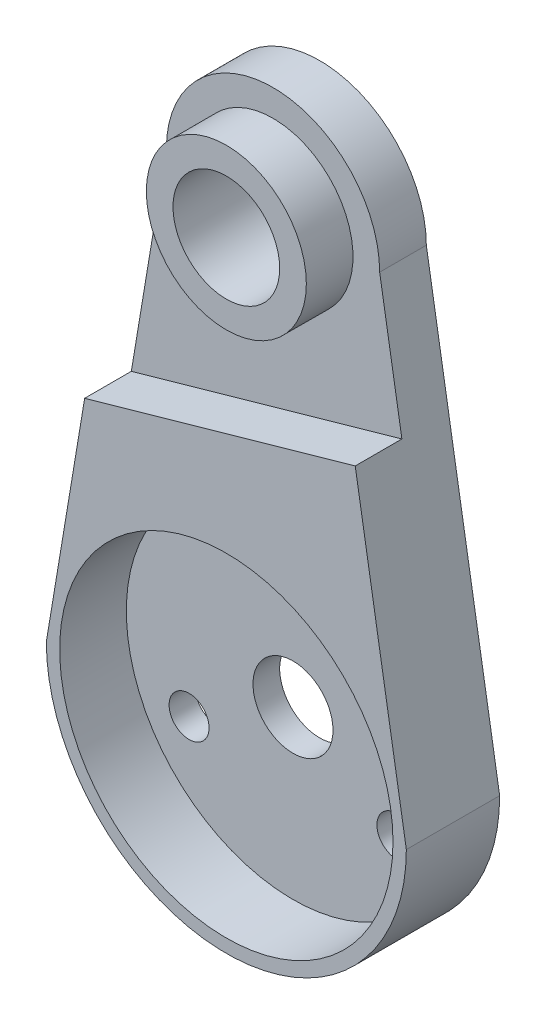
SolidWorks part; units mm, degrees
ref_plane "Plan de face" through (0, 0, 0) normal (0, 0, 1) x (1, 0, 0)
ref_plane "Plan de dessus" through (0, 0, 0) normal (0, 1, 0) x (1, 0, 0)
ref_plane "Plan de droite" through (0, 0, 0) normal (1, 0, 0) x (0, 0, -1)
sketch "Esquisse1" plane through (0, 0, 0) normal (0, 0, 1) x (1, 0, 0)
  line L0 (-16.3093, 0) -> (24.5372, 0) construction
  line L1 (8, 0) -> (13.5, -33)
  line L2 (-8, 0) -> (-13.5, -33)
  line L3 (-13.5, -33) -> (13.5, -33) construction
  line L4 (0, 0) -> (0, -33) construction
  arc A0 (-8, 0) -> (8, 0) centre (0, 0) cw
  arc A1 (-13.5, -33) -> (13.5, -33) centre (0, -33) ccw
  dimension "D1" = 8
  dimension "D2" = 13.5
  dimension "D3" = 33
extrude "Boss.-Extru.1" add sketch "Esquisse1" along normal blind 7
sketch "Esquisse2" plane through (0, 0, 7) normal (0, 0, 1) x (1, 0, 0)
  line L0 (0, 0) -> (0, -46.5) construction
  line L1 (13.5, -33) -> (-13.5, -33) construction
  circle A0 centre (0, -33) radius 3
  arc A1 (-13.5, -33) -> (13.5, -33) centre (0, -33) ccw construction
  dimension "D1" = 6
extrude "Enlèv. mat.-Extru.1" cut sketch "Esquisse2" against normal blind 7
sketch "Esquisse3" plane through (0, 0, 7) normal (0, 0, 1) x (1, 0, 0)
  line L0 (0, -33) -> (0, 0) construction
  line L1 (0, -33) -> (-7.7942, -37.5) construction
  line L2 (0, -33) -> (7.7942, -37.5) construction
  circle A0 centre (0, -24) radius 1.5
  circle A1 centre (-7.7942, -37.5) radius 1.5
  circle A2 centre (7.7942, -37.5) radius 1.5
  dimension "D1" = 3
  dimension "D2" = 3
  dimension "D3" = 3
  dimension "D4" = 9
  dimension "D5" = 9
  dimension "D6" = 9
  dimension "D7" = 120
  dimension "D8" = 120
extrude "Enlèv. mat.-Extru.2" cut sketch "Esquisse3" against normal blind 7
ref_plane "Plan1" through (0, 10, 0) normal (0, 1, 0) x (1, 0, 0)
sketch "Esquisse10" plane through (0, 10, 0) normal (0, 1, 0) x (1, 0, 0)
  line L0 (-13.5, -7) -> (-13.5, 0) construction
  line L1 (13.5, -7) -> (-13.5, -7)
  line L2 (13.5, -7) -> (13.5, -3.5)
  line L3 (13.5, -3.5) -> (-13.5, -3.5)
  line L4 (-13.5, -7) -> (-13.5, -3.5)
  line L5 (-8, -7) -> (-13.5, -7) construction
sketch "Esquisse5" plane through (0, 0, 7) normal (0, 0, 1) x (1, 0, 0)
  circle A0 centre (0, -33) radius 12.5
  dimension "D1" = 25
extrude "Enlèv. mat.-Extru.5" cut sketch "Esquisse5" against normal blind 5
extrude "Enlèv. mat.-Extru.6" cut sketch "Esquisse10" against normal blind 20
sketch "Esquisse12" plane through (0, 0, 3.5) normal (0, 0, 1) x (1, 0, 0)
  circle A0 centre (0, 0) radius 6
  dimension "D1" = 12
extrude "Boss.-Extru.3" add sketch "Esquisse12" along normal blind 3.5
sketch "Esquisse13" plane through (0, 0, 7) normal (0, 0, 1) x (1, 0, 0)
  circle A0 centre (0, 0) radius 4
  dimension "D1" = 8
extrude "Enlèv. mat.-Extru.7" cut sketch "Esquisse13" against normal through all
sketch "Esquisse14" plane through (0, 0, 7) normal (0, 0, 1) x (1, 0, 0)
  line L0 (9.6667, -10) -> (-10.625, -15.75)
  line L4 (-10.625, -15.75) -> (-9.6667, -10)
  line L5 (-9.6667, -10) -> (9.6667, -10)
  line L6 (-9.6667, -10) -> (9.6667, -10) construction
  line L7 (-9.6667, -10) -> (-13.5, -33) construction
  line L8 (-9.6667, -10) -> (-11.5833, -21.5) construction
  line L9 (13.5, -33) -> (9.6667, -10) construction
extrude "Enlèv. mat.-Extru.8" cut sketch "Esquisse14" against normal blind 3.5
